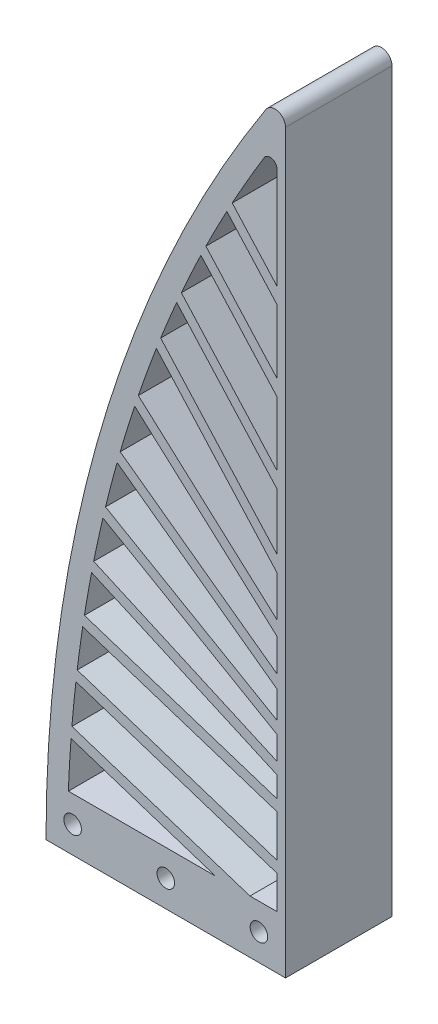
SolidWorks part; units mm, degrees
material "Silicon"
ref_plane "Front Plane" through (0, 0, 0) normal (0, 0, 1) x (1, 0, 0)
ref_plane "Top Plane" through (0, 0, 0) normal (0, 1, 0) x (1, 0, 0)
ref_plane "Right Plane" through (0, 0, 0) normal (1, 0, 0) x (0, 0, -1)
sketch "Sketch1" plane through (0, 0, 0) normal (0, 1, 0) x (1, 0, 0)
  line L1 (-9.5, 8) -> (9.5, 8) construction
  line L2 (-9.5, 8) -> (-9.5, -8) construction
  line L3 (-9.5, -8) -> (9.5, -8) construction
  line L4 (9.5, 8) -> (9.5, -8) construction
  line L5 (-9.5, 8) -> (9.5, -8) construction
  line L6 (-9.5, -8) -> (9.5, 8) construction
  line L7 (12, 10.5) -> (-12, 10.5)
  line L8 (12, 10.5) -> (12, -10.5)
  line L9 (12, -10.5) -> (-12, -10.5)
  line L10 (-12, 10.5) -> (-12, -10.5)
  line L11 (12, 10.5) -> (-12, -10.5) construction
  line L12 (12, -10.5) -> (-12, 10.5) construction
  circle A0 centre (-9.5, 8) radius 1.625
  circle A1 centre (9.5, 8) radius 1.625
  circle A2 centre (9.5, -8) radius 1.625
  circle A3 centre (-9.5, -8) radius 1.625
  point P0 (0, 0)
  point P10 (0, 0)
  dimension "D3" = 3.25
  dimension "D1" = 24
  dimension "D2" = 21
  dimension "D4" = 19
  dimension "D5" = 16
extrude "Boss-Extrude1" [suppressed] add sketch "Sketch1" along normal blind 7.5
sketch "Sketch5" plane through (0, 0, 0) normal (0, 0, 1) x (1, 0, 0)
  line L0 (0, 0) -> (0, 138.4056)
  line L1 (-45, 0) -> (0, 0)
  line L2 (-1.6, 10) -> (-40.8016, 10)
  line L98 (-1.6, 10) -> (-1.6, 130.8055)
  line L99 (-45, 0) -> (-45, 5) construction
  line L102 (-40.9683, 4) -> (-4, 4) construction
  line L103 (-4, 4) -> (-4, 131.4809) construction
  line L104 (0, 0) -> (0, 145) construction
  arc A1 (-3.6773, 139.4949) -> (-45, 0) centre (211.1111, 0) ccw
  arc A24 (-4, 131.4809) -> (-40.8016, 10) centre (211.1111, 0) ccw
  arc A25 (-4, 131.4809) -> (-40.9683, 4) centre (211.1111, 0) ccw construction
  arc A26 (-1.6, 130.8055) -> (-4, 131.4809) centre (-2.895, 130.8055) ccw
  arc A27 (0, 145) -> (-45, 0) centre (211.1111, 0) ccw construction
  arc A28 (0, 138.4056) -> (-3.6773, 139.4949) centre (-2, 138.4056) ccw
  point P16 (0, 145)
  dimension "D7" = 2
  dimension "D2" = 145
  dimension "D5" = 10
  dimension "D6" = 1.6
  dimension "D1" = 5
  dimension "D3" = 45
  dimension "D4" = 4
extrude "Boss-Extrude4" add sketch "Sketch5" along normal blind 20
sketch "Sketch10" plane through (0, 0, 20) normal (0, 0, 1) x (1, 0, 0)
  line L0 (-40.5534, 15) -> (-1.6, 15)
  line L1 (-1.6, 10) -> (-1.6, 130.8055) construction
  line L2 (-1.6, 16.6) -> (-40.4529, 16.6)
  line L3 (-40.8016, 10) -> (-1.6, 10) construction
  line L4 (0, 10) -> (75, 10) construction
  line L5 (0, 0) -> (0, 138.4056) construction
  line L6 (-39.3977, 27.0512) -> (-0.6577, 22.9795)
  line L7 (-0.4905, 24.5707) -> (-39.1306, 28.632)
  line L8 (-36.9887, 38.9156) -> (1.1135, 30.8168)
  line L9 (1.4461, 32.3818) -> (-36.5578, 40.4598)
  line L10 (-33.3527, 50.4632) -> (3.6942, 38.426)
  line L11 (4.1886, 39.9477) -> (-32.7627, 51.9539)
  line L12 (-28.5296, 61.5675) -> (7.0561, 45.7238)
  line L13 (7.7069, 47.1854) -> (-27.787, 62.9883)
  line L14 (-22.5722, 72.1068) -> (11.1625, 52.6301)
  line L15 (11.9625, 54.0158) -> (-21.6851, 73.4422)
  line L20 (0, 68.0707) -> (75, 10) construction
  line L21 (-1.6, 69.3095) -> (-25.2762, 87.6415)
  line L22 (-1.6, 70.9537) -> (-24.7996, 88.9166)
  line L23 (3.8607, 75.76) -> (-18.1278, 96.0857)
  line L24 (4.0039, 77.3979) -> (-17.5418, 97.3144)
  line L25 (9.8627, 81.7099) -> (-10.2705, 103.8747)
  line L26 (10.1482, 83.3291) -> (-9.5797, 105.0477)
  line L27 (16.3605, 87.1142) -> (-1.7643, 110.9493)
  line L28 (16.7861, 88.7023) -> (-0.9739, 112.0576)
  line L29 (23.3046, 91.9315) -> (7.3261, 117.2556)
  line L30 (23.8669, 93.4765) -> (8.2101, 118.2908)
  arc A0 (-4, 131.4809) -> (-40.8016, 10) centre (211.1111, 0) ccw construction
  arc A1 (-4, 131.4809) -> (-40.8016, 10) centre (211.1111, 0) ccw
  point P54 (75, 10)
  point P67 (75, 10)
  dimension "D1" = 1.6
  dimension "D2" = 5
  dimension "D5" = 6
  dimension "D6" = 1.3
  dimension "D9" = 5
  dimension "D7" = 7.75
  dimension "D3" = 121.4809
  dimension "D4" = 6
  dimension "D8" = 5
sketch "Sketch11" plane through (0, 0, 20) normal (0, 0, 1) x (1, 0, 0)
  line L0 (-40.5534, 15) -> (-1.6, 15)
  line L1 (-1.6, 10) -> (-1.6, 130.8055) construction
  line L2 (-1.6, 15) -> (-1.6, 16.6)
  line L3 (-40.4529, 16.6) -> (-1.6, 16.6)
  line L4 (-39.5429, 27.0665) -> (-1.6, 23.0785)
  line L5 (-39.3977, 27.0512) -> (-0.6577, 22.9795) construction
  line L6 (-39.366, 28.6567) -> (-1.6, 24.6873)
  line L7 (-0.4905, 24.5707) -> (-39.1306, 28.632) construction
  line L8 (-37.9465, 39.1192) -> (-1.6, 31.3935)
  line L9 (-37.6929, 40.7011) -> (-1.6, 33.0293)
  line L10 (1.4461, 32.3818) -> (-36.5578, 40.4598) construction
  line L11 (-36.9887, 38.9156) -> (1.1135, 30.8168) construction
  line L12 (-35.7383, 51.2384) -> (-1.6, 40.1462)
  line L13 (-33.3527, 50.4632) -> (3.6942, 38.426) construction
  line L14 (-35.4063, 52.8128) -> (-1.6, 41.8285)
  line L15 (4.1886, 39.9477) -> (-32.7627, 51.9539) construction
  line L16 (-32.8718, 63.5008) -> (-1.6, 49.5777)
  line L17 (-28.5296, 61.5675) -> (7.0561, 45.7238) construction
  line L18 (-32.4585, 65.0682) -> (-1.6, 51.3291)
  line L19 (7.7069, 47.1854) -> (-27.787, 62.9883) construction
  line L29 (-25.2762, 87.6415) -> (-1.6, 69.3095)
  line L31 (-24.7996, 88.9166) -> (-1.6, 70.9537)
  line L33 (-1.6, 61.8461) -> (-28.7801, 77.5385)
  line L35 (-29.2786, 75.9788) -> (-1.6, 59.9985)
  line L36 (-20.899, 98.6474) -> (-1.6, 80.8077)
  line L37 (3.8607, 75.76) -> (-18.1278, 96.0857) construction
  line L38 (-20.3557, 99.9155) -> (-1.6, 82.578)
  line L39 (4.0039, 77.3979) -> (-17.5418, 97.3144) construction
  line L40 (-15.7708, 109.93) -> (-1.6, 94.3293)
  line L41 (9.8627, 81.7099) -> (-10.2705, 103.8747) construction
  line L42 (-15.1571, 111.1878) -> (-1.6, 96.2628)
  line L43 (10.1482, 83.3291) -> (-9.5797, 105.0477) construction
  line L44 (-9.7895, 121.5028) -> (-1.6, 110.7332)
  line L45 (16.3605, 87.1142) -> (-1.7643, 110.9493) construction
  line L46 (-9.1013, 122.7456) -> (-1.6, 112.8809)
  line L47 (16.7861, 88.7023) -> (-0.9739, 112.0576) construction
  line L48 (-1.6, 23.0785) -> (-1.6, 24.6873)
  line L49 (-1.6, 31.3935) -> (-1.6, 33.0293)
  line L50 (-1.6, 40.1462) -> (-1.6, 41.8285)
  line L51 (-1.6, 49.5777) -> (-1.6, 51.3291)
  line L53 (-1.6, 110.7332) -> (-1.6, 112.8809)
  line L54 (-1.6, 94.3293) -> (-1.6, 96.2628)
  line L55 (-1.6, 80.8077) -> (-1.6, 82.578)
  line L59 (-22.5722, 72.1068) -> (11.1625, 52.6301) construction
  line L60 (11.9625, 54.0158) -> (-21.6851, 73.4422) construction
  line L61 (-1.6, 59.9985) -> (-1.6, 61.8461)
  line L62 (-2.8376, 133.364) -> (-1.6, 131.4025)
  line L63 (-2.0713, 134.5856) -> (-1.6, 133.8387)
  line L64 (23.8669, 93.4765) -> (8.2101, 118.2908) construction
  line L65 (23.3046, 91.9315) -> (7.3261, 117.2556) construction
  line L66 (-1.6, 133.8387) -> (-1.6, 131.4025)
  arc A0 (-4, 131.4809) -> (-40.8016, 10) centre (211.1111, 0) ccw construction
  arc A2 (-40.4529, 16.6) -> (-40.5534, 15) centre (211.1111, 0) ccw
  arc A8 (-20.3557, 99.9155) -> (-20.899, 98.6474) centre (211.1111, 0) ccw
  arc A13 (-2.0713, 134.5856) -> (-2.8376, 133.364) centre (211.1111, 0) ccw
  arc A14 (-40.4529, 16.6) -> (-40.5534, 15) centre (211.1111, 0) ccw
  arc A15 (-39.366, 28.6567) -> (-39.5429, 27.0665) centre (211.1111, 0) ccw
  arc A16 (-37.6929, 40.7011) -> (-37.9465, 39.1192) centre (211.1111, 0) ccw
  arc A17 (-35.4063, 52.8128) -> (-35.7383, 51.2384) centre (211.1111, 0) ccw
  arc A18 (-32.4585, 65.0682) -> (-32.8718, 63.5008) centre (211.1111, 0) ccw
  arc A19 (-28.7801, 77.5385) -> (-29.2786, 75.9788) centre (211.1111, 0) ccw
  arc A20 (-24.7996, 88.9166) -> (-25.2762, 87.6415) centre (211.1111, 0) ccw
  arc A21 (-20.3557, 99.9155) -> (-20.899, 98.6474) centre (211.1111, 0) ccw
  arc A22 (-15.1571, 111.1878) -> (-15.7708, 109.93) centre (211.1111, 0) ccw
  arc A23 (-9.1013, 122.7456) -> (-9.7895, 121.5028) centre (211.1111, 0) ccw
sketch "Sketch12" plane through (0, 0, 20) normal (0, 0, 1) x (1, 0, 0)
  line L0 (-40, 5) -> (-22.5, 5) construction
  line L1 (-40.8016, 10) -> (-1.6, 10) construction
  line L2 (-22.5, 0) -> (-22.5, 10) construction
  line L3 (-45, 0) -> (0, 0) construction
  line L4 (-22.5, 5) -> (-5, 5) construction
  line L6 (-5, 5) -> (0, 5) construction
  line L7 (0, 0) -> (0, 138.4056) construction
  circle A1 centre (-40, 5) radius 1.65
  circle A2 centre (-22.5, 5) radius 1.65
  circle A3 centre (-5, 5) radius 1.65
  dimension "D1" = 3.3
  dimension "D2" = 17.5
extrude "Cut-Extrude1" cut sketch "Sketch12" against normal through all
sketch "Sketch14" plane through (0, 0, 20) normal (0, 0, 1) x (1, 0, 0)
  line L1 (48.4, 10) -> (-114.1015, 62.7999)
  line L6 (48.4, 10) -> (49.018, 11.9021)
  line L7 (-114.1015, 62.7999) -> (-113.4835, 64.702)
  line L8 (49.018, 11.9021) -> (-113.4835, 64.702)
  line L9 (-40.8016, 10) -> (-1.6, 10) construction
  dimension "D1" = 0
  dimension "D2" = 2
  dimension "D3" = 50
  dimension "D4" = 18
sketch "Sketch17" plane through (0, 0, 20) normal (0, 0, 1) x (1, 0, 0)
  line L0 (-45, 0) -> (0, 0)
  line L1 (0, 0) -> (0, 138.4056)
  line L3 (-109.1292, -31.174) -> (890.8708, -18.3863)
  line L4 (890.8708, -18.3863) -> (884.1337, 508.4542)
  line L5 (884.1337, 508.4542) -> (-120.6382, 868.826)
  line L6 (-120.6382, 868.826) -> (-717.4627, 272.0014)
  line L7 (-717.4627, 272.0014) -> (-109.1292, -31.174)
  arc A1 (0, 138.4056) -> (-2.7696, 140.2516) centre (-2, 138.4056) ccw
  arc A3 (-2.7696, 140.2516) -> (-45, 0) centre (33.6937, 52.7886) ccw
  dimension "D1" = 900
  dimension "D2" = 1000
extrude "Cut-Extrude2" cut sketch "Sketch17" against normal blind 20
sketch "Sketch18" plane through (0, 0, 20) normal (0, 0, 1) x (1, 0, 0)
  line L0 (-45, 0) -> (0, 0)
  line L1 (0, 0) -> (0, 138.4056)
  line L2 (10.5677, -7.1526) -> (26.572, 318.7821)
  line L3 (26.572, 318.7821) -> (-234.7297, 306.4711)
  line L4 (-234.7297, 306.4711) -> (-205.7988, -46.8557)
  line L5 (-205.7988, -46.8557) -> (10.5677, -7.1526)
  arc A0 (0, 138.4056) -> (-3.6773, 139.4949) centre (-2, 138.4056) ccw
  arc A1 (-3.6773, 139.4949) -> (-45, 0) centre (211.1111, 0) ccw
extrude "Cut-Extrude3" cut sketch "Sketch18" against normal blind 30
extrude "Boss-Extrude5" add sketch "Sketch14" against normal blind 20
pattern_circular "CirPattern1" count 6 every 6 about axis through (49.018, 11.9021, 0) along (0, 0, 1) of "Boss-Extrude5"
pattern_linear "LPattern2" count 3 spacing 10 along (0, -1, 0) of "Boss-Extrude5"
sketch "Sketch19" plane through (0, 0, 20) normal (0, 0, 1) x (1, 0, 0)
  line L0 (-1.6, 78.7581) -> (-60.025, 143.6457)
  line L1 (-1.6, 78.7581) -> (-0.1137, 80.0964)
  line L2 (-60.025, 143.6457) -> (-58.5387, 144.9839)
  line L3 (-0.1137, 80.0964) -> (-58.5387, 144.9839)
  line L4 (-1.6, 68.1191) -> (-1.6, 130.8055) construction
  line L5 (-26.4438, 95.7109) -> (-65.3124, 138.8789) construction
  line L6 (-1.6, 68.1191) -> (-23.4588, 92.3958) construction
  dimension "D1" = 0
  dimension "D2" = 7.1189
  dimension "D3" = 2
extrude "Boss-Extrude6" add sketch "Sketch19" against normal blind 20
pattern_linear "LPattern3" count 3 spacing 15 along (0, 1, 0) of "Boss-Extrude6"
sketch "Sketch20" plane through (0, 0, 20) normal (0, 0, 1) x (1, 0, 0)
  line L0 (-45, 0) -> (0, 0)
  line L1 (0, 0) -> (0, 138.4056)
  line L2 (77.4758, -29.0172) -> (-265.5513, 6.5235)
  line L3 (-265.5513, 6.5235) -> (-137.3654, 367.5206)
  line L4 (-137.3654, 367.5206) -> (154.1478, 113.1454)
  line L5 (154.1478, 113.1454) -> (77.4758, -29.0172)
  arc A0 (0, 138.4056) -> (-3.6773, 139.4949) centre (-2, 138.4056) ccw
  arc A1 (-3.6773, 139.4949) -> (-45, 0) centre (211.1111, 0) ccw
extrude "Cut-Extrude4" cut sketch "Sketch20" against normal blind 20
equation "\"Middle Finger Width\"= 30mm"
equation "\"Finger Length\"= 45"
equation "\"Finger Height\"= \"Finger Length\" * 3.5"
equation "\"D3@Sketch5\"=\"Finger Length\""
equation "\"Base Height\"= 10mm"
equation "\"D1@Sketch5\"= \"Base Height\" / 2"
equation "\"D5@Sketch5\"= \"Base Height\""
equation "\"Thick Walls\"= 1.6mm"
equation "\"Thin Walls\"= 1.3mm"
equation "\"D6@Sketch5\"=\"Thick Walls\""
equation "\"D2@Sketch10\"=\"Base Height\"/2"
equation "\"D1@Sketch10\"=\"Thick Walls\" "
equation "\"D6@Sketch10\"=\"Thin Walls\""
equation "\"D1@Boss-Extrude4\"  = 2 * \"Middle Finger Width\" /3"
equation "\"Outer Finger Width\"= 2 * \"Middle Finger Width\" / 3"
